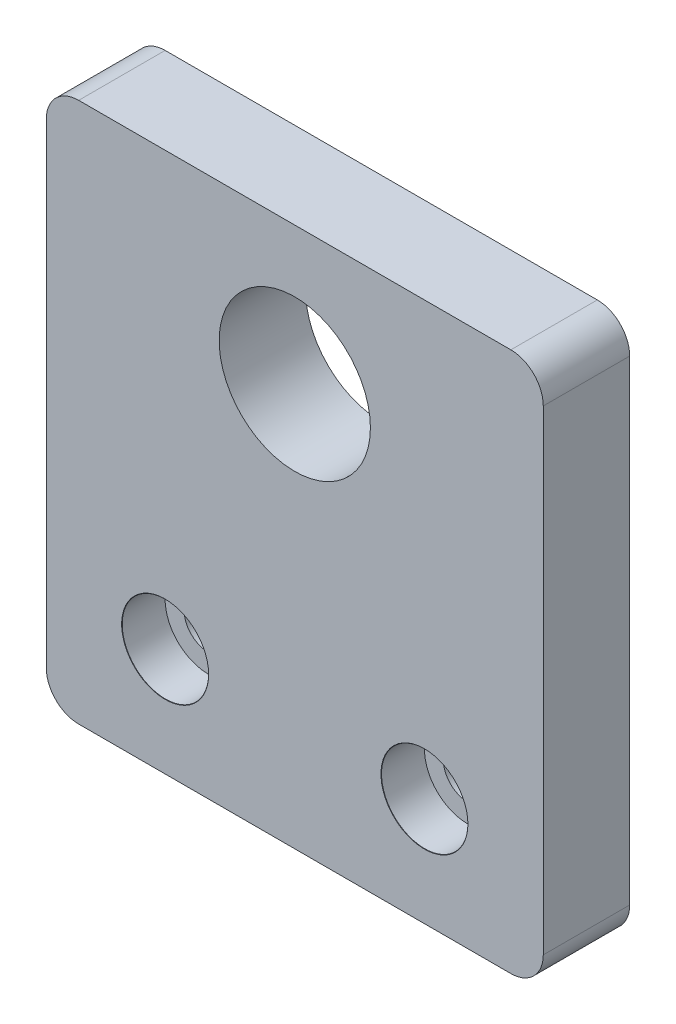
SolidWorks part; units mm, degrees
ref_plane "Front" through (0, 0, 0) normal (0, 0, 1) x (1, 0, 0)
ref_plane "Top" through (0, 0, 0) normal (0, 1, 0) x (1, 0, 0)
ref_plane "Right" through (0, 0, 0) normal (1, 0, 0) x (0, 0, -1)
sketch "Sketch1" plane through (0, 0, 0) normal (0, 0, 1) x (1, 0, 0)
  line L0 (-16.7, -15.095) -> (-7.5, -15.095) construction
  line L1 (-23, -25) -> (23, -25)
  line L2 (-23, -25) -> (-23, 25)
  line L3 (-23, 25) -> (23, 25)
  line L4 (23, -25) -> (23, 25)
  line L5 (-23, -25) -> (23, 25) construction
  line L6 (-23, 25) -> (23, -25) construction
  line L8 (-12.1, 25) -> (-12.1, -10.19) construction
  line L9 (-12.1, -10.19) -> (-12.1, -20) construction
  line L10 (-12.1, -20) -> (-12.1, -25) construction
  line L11 (-12, -15) -> (12, -15) construction
  line L12 (0, 0) -> (0, -15) construction
  line L13 (0, 19) -> (0, 4.85) construction
  circle A1 centre (0, 12.25) radius 7
  point P0 (0, 0)
  point P9 (0, 30.2982)
  point P12 (-12.1, -15.095)
  point P17 (0, 0)
  point P23 (0, 11.925)
  point P24 (4.965, -15.095)
  point P25 (0, 11.925)
  point P26 (0, 0)
  point P27 (0, 11.925)
  point P28 (0, 0)
  dimension "D7" = 6
  dimension "D9" = 14
  dimension "D1" = 46
  dimension "D2" = 50
  dimension "D3" = 5
  dimension "D4" = 35.19
  dimension "D5" = 6.3
  dimension "D6" = 30.5
  dimension "D8" = 29.85
  dimension "D10" = 10
  dimension "D11" = 24
  dimension "D12" = 37.25
extrude "Boss-Extrude1" add sketch "Sketch1" along normal blind 8
fillet "Fillet1" radius 3 4 edges at (23, -25, 4) (-23, -25, 4) (-23, 25, 4) (23, 25, 4)
hole_wizard "CBORE for M4 SHCS1" positions "Sketch2" profile "Sketch3" counterbore size "M4" standard "ANSI Metric" end condition through all
sketch "Sketch2" plane through (0, 0, 8) normal (0, 0, 1) x (1, 0, 0)
  point P0 (-12, -15)
  point P3 (12, -15)
  point P7 (0, 0)
  point P8 (-12, -15)
sketch "Sketch3" plane through (-12, -15, 8) normal (1, 0, 0) x (0, -1, 0)
  line L0 (0, 0) -> (0, 8)
  line L1 (0, 8) -> (2.25, 8)
  line L3 (2.25, 8) -> (2.25, 4)
  line L4 (4, 4) -> (2.25, 4)
  line L5 (4, 4) -> (4, 0.025)
  line L6 (4, 0.025) -> (4.025, 0)
  line L7 (4.025, 0) -> (0, 0)
  line L8 (-4, 0.025) -> (-4.025, 0) construction
  line L11 (0, -6.35) -> (0, 107.95) construction
  dimension "Thru Hole Dia." = 4.5
  dimension "Thru Hole Depth" = 8
  dimension "C'Bore Dia." = 8
  dimension "C'Bore Depth" = 4
  dimension "Near C'Sink Dia." = 8.05
  dimension "Near C'Sink Angle" = 90
